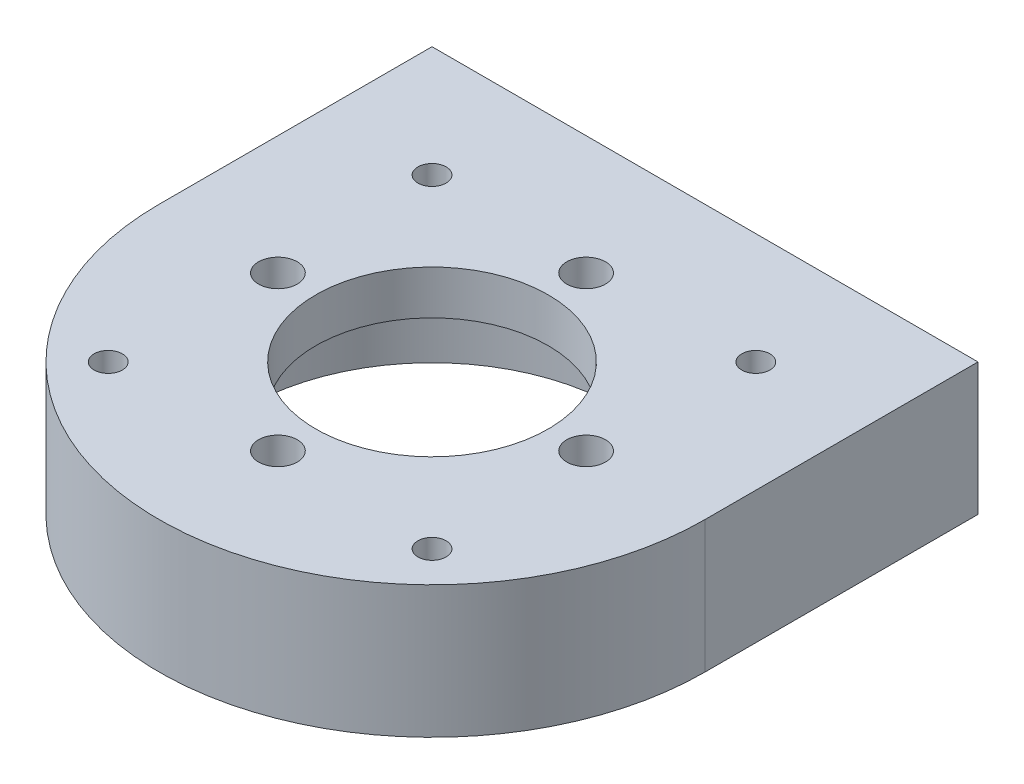
SolidWorks part; units mm, degrees
ref_plane "前视基准面" through (0, 0, 0) normal (0, 0, 1) x (1, 0, 0)
ref_plane "上视基准面" through (0, 0, 0) normal (0, 1, 0) x (1, 0, 0)
ref_plane "右视基准面" through (0, 0, 0) normal (1, 0, 0) x (0, 0, -1)
sketch "草图1" plane through (0, 0, 0) normal (0, 1, 0) x (1, 0, 0)
  line L0 (-31, 0) -> (-31, 31)
  line L1 (-31, 31) -> (31, 31)
  line L2 (31, 31) -> (31, 0)
  line L3 (-31, 31) -> (-31, 46)
  line L4 (-31, 46) -> (31, 46)
  line L5 (31, 46) -> (31, 31)
  line L6 (-31, 38.5) -> (-25, 38.5) construction
  line L7 (-25, 38.5) -> (0, 38.5) construction
  line L8 (0, 38.5) -> (25, 38.5) construction
  line L9 (25, 38.5) -> (31, 38.5) construction
  line L10 (0, 0) -> (0, 26) construction
  line L11 (0, 0) -> (18.3848, 18.3848) construction
  circle A0 centre (0, 0) radius 31
  circle A1 centre (0, 0) radius 21.1
  circle A2 centre (0, 0) radius 13.1
  circle A3 centre (0, 0) radius 17.5 construction
  circle A4 centre (0, 17.5) radius 2.1
  circle A5 centre (-17.5, 0) radius 2.1
  circle A6 centre (0, -17.5) radius 2.1
  circle A7 centre (17.5, 0) radius 2.1
  circle A8 centre (-25, 38.5) radius 1.6
  circle A9 centre (0, 38.5) radius 1.6
  circle A10 centre (25, 38.5) radius 1.6
  circle A11 centre (0, 0) radius 26 construction
  circle A12 centre (18.3848, 18.3848) radius 1.6
  circle A13 centre (18.3848, -18.3848) radius 1.6
  circle A14 centre (-18.3848, -18.3848) radius 1.6
  circle A15 centre (-18.3848, 18.3848) radius 1.6
  dimension "D3" = 42.2
  dimension "D4" = 26.2
  dimension "D5" = 35
  dimension "D6" = 4.2
  dimension "D8" = 3.2
  dimension "D9" = 52
  dimension "D1" = 31
  dimension "D2" = 15
  dimension "D7" = 6
  dimension "D10" = 45
  dimension "D11" = 4
extrude "凸台-拉伸1" add sketch "草图1" along normal blind 15 contours A0 A15 A14 A13 A12 A1 | A0 L1 L0 | A0 L2 L1
sketch "草图2" plane through (0, 0, 0) normal (0, -1, 0) x (1, 0, 0)
  circle A0 centre (0, 0) radius 21.1
  circle A1 centre (0, 0) radius 21.1 construction
  circle A2 centre (0, 0) radius 13.2
  circle A3 centre (0, 0) radius 17.5 construction
  circle A4 centre (0, 17.5) radius 2.2
  circle A5 centre (17.5, 0) radius 2.2
  circle A6 centre (0, -17.5) radius 2.2
  circle A7 centre (-17.5, 0) radius 2.2
  point P9 (-17.5, 0)
  point P18 (0, 0)
  dimension "D1" = 26.4
  dimension "D2" = 4.4
  dimension "D3" = 35
  dimension "D4" = 4
extrude "凸台-拉伸2" add sketch "草图2" against normal blind 5 from offset 10
